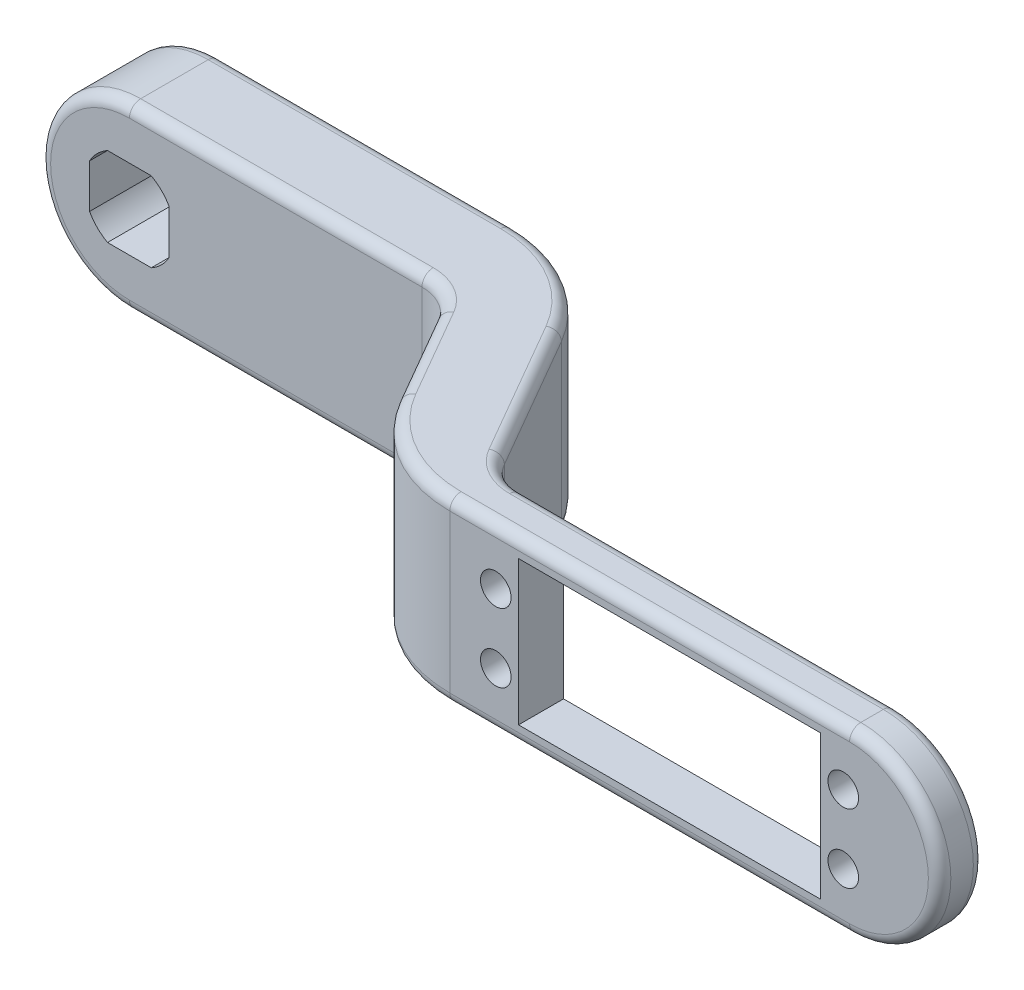
SolidWorks part; units mm, degrees
ref_plane "Front Plane" through (0, 0, 0) normal (0, 0, 1) x (1, 0, 0)
ref_plane "Top Plane" through (0, 0, 0) normal (0, 1, 0) x (1, 0, 0)
ref_plane "Right Plane" through (0, 0, 0) normal (1, 0, 0) x (0, 0, -1)
sketch "Sketch1" plane through (0, 0, 0) normal (0, 1, 0) x (1, 0, 0)
  line L0 (0, 0) -> (53.975, 0) construction
  line L1 (64.9735, -6.35) -> (72.3059, -19.05) construction
  line L2 (83.3044, -25.4) -> (152.4, -25.4)
  line L3 (0, -6.35) -> (53.975, -6.35)
  line L4 (59.4743, -9.525) -> (66.8066, -22.225)
  line L6 (0, 6.35) -> (53.975, 6.35)
  line L7 (70.4728, -3.175) -> (77.8051, -15.875)
  line L9 (0, -6.35) -> (0, 6.35)
  line L11 (83.3044, -19.05) -> (152.4, -19.05) construction
  line L12 (83.3044, -31.75) -> (152.4, -31.75) construction
  line L19 (83.3044, -31.75) -> (152.4, -31.75)
  line L20 (83.3044, -31.75) -> (152.4, -31.75) construction
  line L21 (152.4, -25.4) -> (152.4, -31.75)
  line L23 (77.8051, -15.875) -> (83.3044, -25.4)
  arc A0 (53.975, 0) -> (64.9735, -6.35) centre (53.975, -12.7) cw construction
  arc A1 (72.3059, -19.05) -> (83.3044, -25.4) centre (83.3044, -12.7) ccw construction
  arc A2 (53.975, -6.35) -> (59.4743, -9.525) centre (53.975, -12.7) cw
  arc A3 (66.8066, -22.225) -> (83.3044, -31.75) centre (83.3044, -12.7) ccw
  arc A4 (53.975, 6.35) -> (70.4728, -3.175) centre (53.975, -12.7) cw
  arc A6 (77.8051, -15.875) -> (83.3044, -19.05) centre (83.3044, -12.7) ccw construction
  dimension "D4" = 12.7
  dimension "D1" = 53.975
  dimension "D2" = 152.4
  dimension "D3" = 25.4
  dimension "D5" = 60
  dimension "D6" = 6.35
  dimension "D7" = 6.35
  dimension "D8" = 6.35
extrude "Boss-Extrude1" add sketch "Sketch1" along normal blind 25.4
ref_plane "Plane1" through (0, 25.4, 6.35) normal (0, -1, 0) x (-1, 0, 0)
sketch "Sketch3" plane through (0, 0, 6.35) normal (0, 0, 1) x (1, 0, 0)
  line L0 (0, 25.4) -> (0, 0) construction
  line L2 (7.0802, 7.0802) -> (18.3197, 7.0802)
  line L3 (7.0802, 7.0802) -> (7.0802, 18.3197)
  line L4 (7.0802, 18.3197) -> (18.3197, 18.3197)
  line L5 (18.3197, 7.0802) -> (18.3197, 18.3197)
  line L6 (7.0802, 7.0802) -> (18.3197, 18.3197) construction
  line L7 (7.0802, 18.3197) -> (18.3197, 7.0802) construction
  circle A0 centre (12.7, 12.7) radius 6.4135
  point P5 (0, 12.7)
  dimension "D1" = 12.827
  dimension "D2" = 11.2395
  dimension "D3" = 12.7
extrude "Cut-Extrude1" cut sketch "Sketch3" against normal blind 25.4 contours L5 A0 L4 L3 L2
sketch "Sketch4" plane through (0, 0, 6.35) normal (0, 0, 1) x (1, 0, 0)
  line L5 (0, 0) -> (53.975, 0)
  line L6 (53.975, 0) -> (53.975, 25.4)
  line L7 (0, 0) -> (53.975, 0)
  line L8 (0, 25.4) -> (0, 0)
  line L12 (0, 25.4) -> (0, 0)
  line L13 (53.975, 25.4) -> (0, 25.4)
  line L14 (53.975, 25.4) -> (0, 25.4)
  arc A0 (12.7, 25.4) -> (12.7, 0) centre (12.7, 12.7) ccw
  arc A1 (18.3197, 15.7905) -> (15.7905, 18.3197) centre (12.7, 12.7) ccw construction
  dimension "D1" = 0
extrude "Cut-Extrude2" cut sketch "Sketch4" against normal up to next
sketch "Sketch7" plane through (0, 0, 31.75) normal (0, 0, 1) x (1, 0, 0)
  line L1 (83.3044, 25.4) -> (152.4, 25.4) construction
  line L2 (152.4, 25.4) -> (152.4, 0) construction
  line L3 (83.3044, 0) -> (152.4, 0) construction
  line L4 (139.7, 0) -> (152.4, 0)
  line L5 (152.4, 25.4) -> (152.4, 0)
  line L6 (139.7, 25.4) -> (152.4, 25.4)
  arc A0 (139.7, 0) -> (139.7, 25.4) centre (139.7, 12.7) ccw
  line M2 (83.3044, 0) -> (152.4, 0)
  line M3 (152.4, 0) -> (152.4, 25.4)
  line M4 (152.4, 25.4) -> (83.3044, 25.4)
extrude "Cut-Extrude6" cut sketch "Sketch7" against normal up to next contours A0 L5 M4 | A0 M2 M3
sketch "Sketch8" plane through (0, 0, 31.75) normal (0, 0, 1) x (1, 0, 0)
  line L0 (114.3, 22.86) -> (114.3, 2.54) construction
  line L1 (92.9958, 2.54) -> (135.6043, 2.54)
  line L2 (92.9958, 2.54) -> (92.9958, 22.86)
  line L3 (92.9958, 22.86) -> (135.6043, 22.86)
  line L4 (135.6043, 2.54) -> (135.6043, 22.86)
  line L5 (92.9958, 2.54) -> (135.6043, 22.86) construction
  line L6 (92.9958, 22.86) -> (135.6043, 2.54) construction
  line L7 (89.789, 7.8486) -> (89.789, 17.5514) construction
  circle A0 centre (138.811, 7.8486) radius 2.159
  circle A1 centre (138.811, 17.5514) radius 2.159
  circle A2 centre (89.789, 7.8486) radius 2.159
  circle A3 centre (89.789, 17.5514) radius 2.159
  arc A4 (139.7, 0) -> (139.7, 25.4) centre (139.7, 12.7) ccw construction
  point P0 (114.3, 12.7)
  point P13 (139.7, 12.7)
  point P16 (89.789, 12.7)
  dimension "D1" = 4.318
  dimension "D2" = 42.6085
  dimension "D3" = 20.32
  dimension "D4" = 9.7028
  dimension "D5" = 49.022
  dimension "D6" = 25.4
extrude "Cut-Extrude7" cut sketch "Sketch8" against normal up to next
fillet "Fillet2" radius 6.35 1 edges at (83.3044, 12.7, 25.4)
fillet "Fillet1" radius 1.5875 24 edges at (0, 12.7, 6.35) (33.3375, 0, 6.35) (57.15, 0, 7.2007) (63.1404, 0, 15.875) (73.7794, 0, 29.1978) (111.5022, 0, 31.75) (152.4, 12.7, 31.75) (111.5022, 25.4, 31.75) (73.7794, 25.4, 29.1978) (63.1404, 25.4, 15.875) (57.15, 25.4, 7.2007) (75.972, 0, 12.7) (63.5, 0, -3.7978) (33.3375, 0, -6.35) (0, 12.7, -6.35) (75.972, 25.4, 12.7) (63.5, 25.4, -3.7978) (33.3375, 25.4, 6.35) (33.3375, 25.4, -6.35) (83.7956, 0, 24.5493) (113.3353, 0, 25.4) (152.4, 12.7, 25.4) (113.3353, 25.4, 25.4) (83.7956, 25.4, 24.5493)
